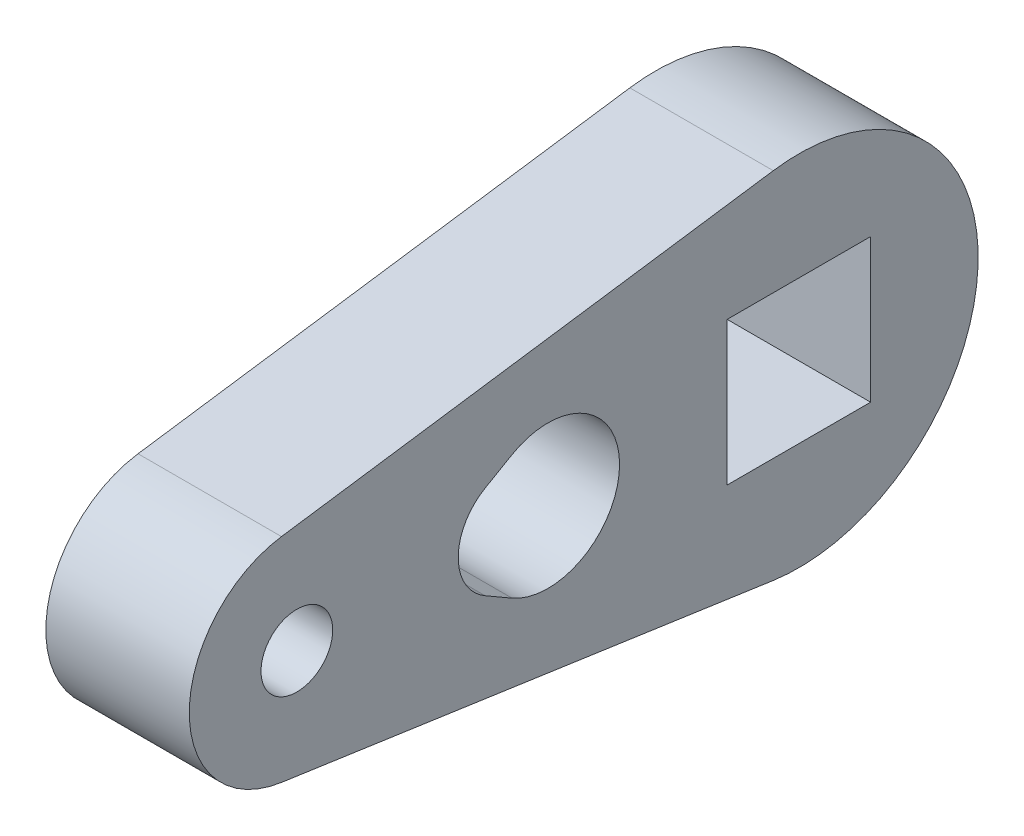
SolidWorks part; units mm, degrees
material "1060 合金"
ref_plane "前视基准面" through (0, 0, 0) normal (0, 0, 1) x (1, 0, 0)
ref_plane "上视基准面" through (0, 0, 0) normal (0, 1, 0) x (1, 0, 0)
ref_plane "右视基准面" through (0, 0, 0) normal (1, 0, 0) x (0, 0, -1)
sketch "草图1" plane through (0, 0, 0) normal (1, 0, 0) x (0, 0, -1)
  line L0 (-28.8571, 5.9385) -> (-1.4286, 9.8974)
  line L1 (-4, 4) -> (4, 4)
  line L2 (-4, 4) -> (-4, -4)
  line L3 (-4, -4) -> (4, -4)
  line L4 (4, 4) -> (4, -4)
  line L5 (-28.8571, -5.9385) -> (-1.4286, -9.8974)
  line L6 (-17.5, 2.5981) -> (-16, 3.4641)
  line L7 (-17.5, -2.5981) -> (-16, -3.4641)
  arc A0 (-1.4286, -9.8974) -> (-1.4286, 9.8974) centre (0, 0) ccw
  arc A1 (-28.8571, 5.9385) -> (-28.8571, -5.9385) centre (-28, 0) ccw
  arc A2 (-17.5, 2.5981) -> (-17.5, -2.5981) centre (-16, 0) ccw
  arc A3 (-16, -3.4641) -> (-16, 3.4641) centre (-14, 0) ccw
  circle A4 centre (-28, 0) radius 2
  point P8 (4, 0)
  point P15 (0, 4)
  dimension "D2" = 10
  dimension "D4" = 4
  dimension "D5" = 3
  dimension "D8" = 4
  dimension "D9" = 6
  dimension "D1" = 8
  dimension "D3" = 28
  dimension "D6" = 14
  dimension "D7" = 12
extrude "凸台-拉伸1" add sketch "草图1" along normal mid plane 8
